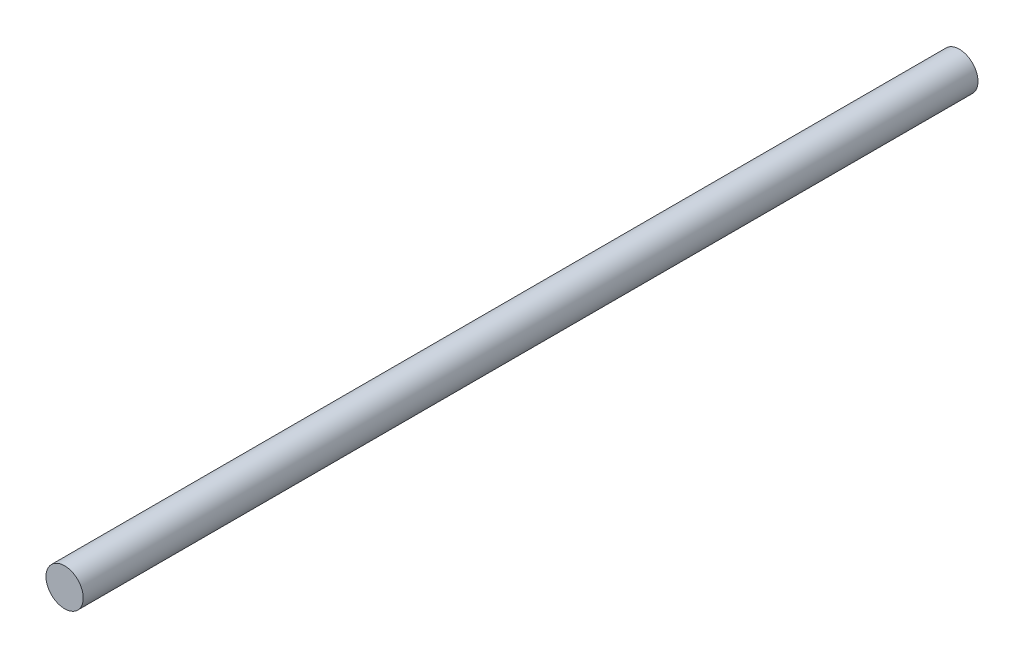
SolidWorks part; units mm, degrees
ref_plane "Plan de face" through (0, 0, 0) normal (0, 0, 1) x (1, 0, 0)
ref_plane "Plan de dessus" through (0, 0, 0) normal (0, 1, 0) x (1, 0, 0)
ref_plane "Plan de droite" through (0, 0, 0) normal (1, 0, 0) x (0, 0, -1)
sketch "Esquisse1" plane through (0, 0, 0) normal (0, 0, 1) x (1, 0, 0)
  circle A0 centre (0, 0) radius 5
  dimension "D1" = 10
extrude "Boss.-Extru.1" add sketch "Esquisse1" along normal blind 240
